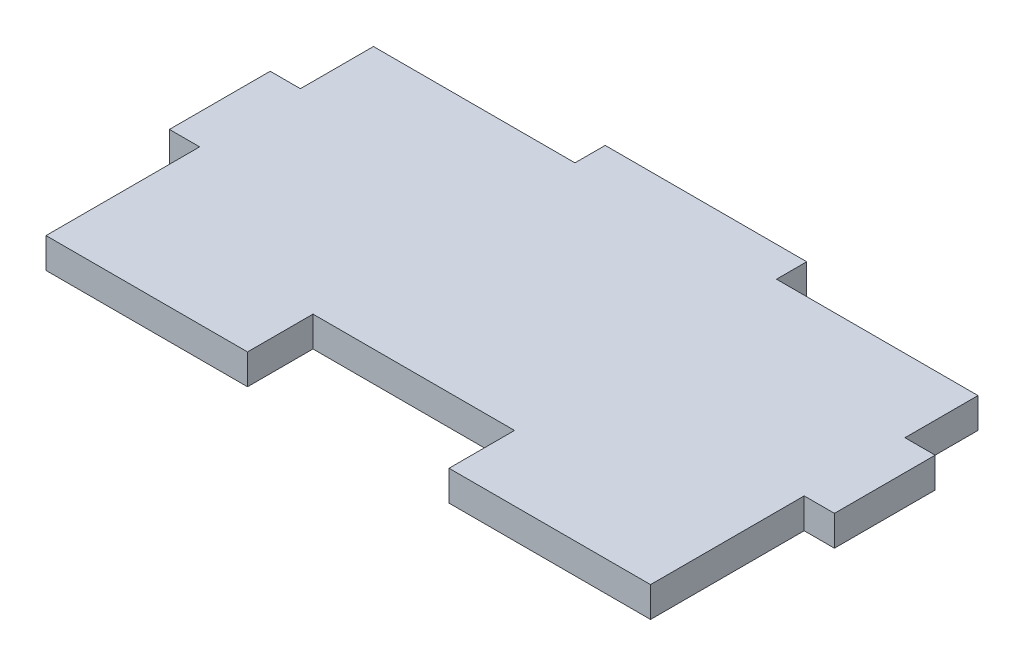
SolidWorks part; units mm, degrees
ref_plane "Front Plane" through (0, 0, 0) normal (0, 0, 1) x (1, 0, 0)
ref_plane "Top Plane" through (0, 0, 0) normal (0, 1, 0) x (1, 0, 0)
ref_plane "Right Plane" through (0, 0, 0) normal (1, 0, 0) x (0, 0, -1)
sketch "Sketch2" plane through (0, 0, 0) normal (0, 1, 0) x (1, 0, 0)
  line L1 (-30, 17.75) -> (30, 17.75)
  line L2 (-30, 17.75) -> (-30, -17.75)
  line L3 (-30, -17.75) -> (30, -17.75)
  line L4 (30, 17.75) -> (30, -17.75)
  line L5 (-30, 17.75) -> (30, -17.75) construction
  line L6 (-30, -17.75) -> (30, 17.75) construction
  point P0 (0, 0)
  dimension "D1" = 60
  dimension "D2" = 35.5
extrude "Boss-Extrude1" add sketch "Sketch2" along normal blind 3
sketch "Sketch3" plane through (0, 0, 0) normal (0, 1, 0) x (1, 0, 0)
  line L0 (-30, 7.5) -> (-33, 7.5)
  line L1 (-30, 17.75) -> (-30, -17.75) construction
  line L2 (-33, 7.5) -> (-33, -2.5)
  line L3 (-33, -2.5) -> (-30, -2.5)
  line L4 (-30, -2.5) -> (-30, 7.5)
  line L5 (30, 7.5) -> (33, 7.5)
  line L6 (30, -17.75) -> (30, 17.75) construction
  line L7 (33, 7.5) -> (33, -2.5)
  line L8 (33, -2.5) -> (30, -2.5)
  line L9 (30, -2.5) -> (30, 7.5)
  line L10 (30, 17.75) -> (-30, 17.75) construction
  point P10 (33, 2.5)
  point P13 (-33, 2.5)
  dimension "D1" = 3
  dimension "D2" = 10
  dimension "D3" = 15.25
  dimension "D4" = 15.25
extrude "Boss-Extrude2" add sketch "Sketch3" along normal blind 3
sketch "Sketch4" plane through (0, 3, 0) normal (0, 1, 0) x (1, 0, 0)
  line L0 (-10, 17.75) -> (-10, 14.75)
  line L1 (30, 17.75) -> (-30, 17.75) construction
  line L2 (-10, 14.75) -> (10, 14.75)
  line L3 (10, 14.75) -> (10, 17.75)
  line L4 (0, 14.75) -> (0, 17.75) construction
  line L5 (-10, 17.75) -> (10, 17.75)
  line L6 (-10, 14.75) -> (-30, 14.75)
  line L7 (-30, 17.75) -> (-30, 7.5) construction
  line L8 (-30, 14.75) -> (-30, 17.75)
  line L9 (-30, 17.75) -> (-10, 17.75)
  line L10 (10, 14.75) -> (30, 14.75)
  line L11 (30, 7.5) -> (30, 17.75) construction
  line L12 (30, 14.75) -> (30, 17.75)
  line L13 (30, 17.75) -> (10, 17.75)
  line M8 (30, 7.5) -> (30, 17.75)
  line M9 (30, 17.75) -> (-30, 17.75)
  line M10 (-30, 17.75) -> (-30, 7.5)
  dimension "D1" = 3
  dimension "D2" = 20
extrude "Cut-Extrude2" cut sketch "Sketch4" against normal blind 3 contours L6 L0 M9 M10 | L3 L10 M8 M9
sketch "Sketch5" plane through (0, 3, 0) normal (0, 1, 0) x (1, 0, 0)
  line L0 (-10, -17.75) -> (-10, -11.25)
  line L1 (-30, -17.75) -> (30, -17.75) construction
  line L2 (-10, -11.25) -> (10, -11.25)
  line L3 (10, -11.25) -> (10, -17.75)
  line L4 (10, -17.75) -> (-10, -17.75)
  line L5 (0, -11.25) -> (0, -17.75) construction
  dimension "D1" = 20
  dimension "D2" = 6.5
extrude "Cut-Extrude3" cut sketch "Sketch5" against normal blind 10
